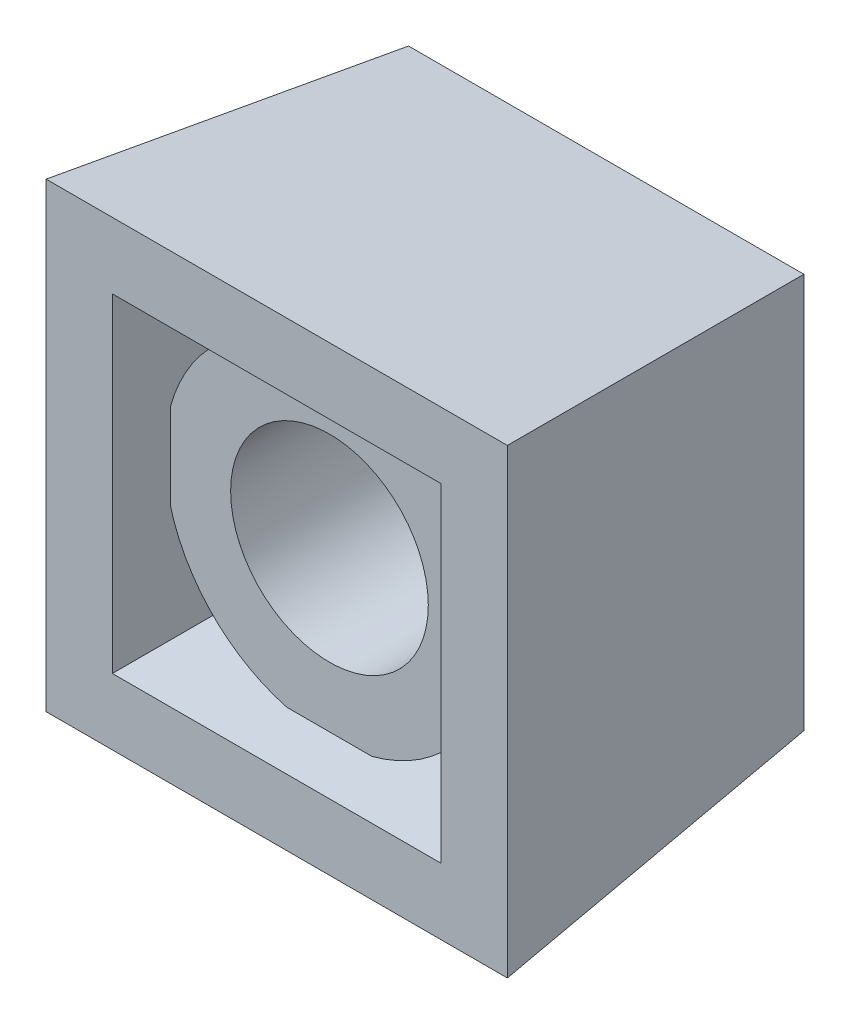
SolidWorks part; units mm, degrees
ref_plane "Plan de face" through (0, 0, 0) normal (0, 0, 1) x (1, 0, 0)
ref_plane "Plan de dessus" through (0, 0, 0) normal (0, 1, 0) x (1, 0, 0)
ref_plane "Plan de droite" through (0, 0, 0) normal (1, 0, 0) x (0, 0, -1)
sketch "Esquisse1" plane through (0, 0, 0) normal (0, 0, 1) x (1, 0, 0)
  line L1 (-3, 3) -> (3, 3)
  line L2 (-3, 3) -> (-3, -3)
  line L3 (-3, -3) -> (3, -3)
  line L4 (3, 3) -> (3, -3)
  line L5 (-3, 3) -> (3, -3) construction
  line L6 (-3, -3) -> (3, 3) construction
  point P0 (0, 0)
  dimension "D1" = 6
ref_plane "Plan1" through (0, 0, 5) normal (0, 0, 1) x (1, 0, 0)
sketch "Esquisse2" plane through (0, 0, 5) normal (0, 0, 1) x (1, 0, 0)
  line L1 (3.5, 3.5) -> (-3.5, 3.5)
  line L2 (3.5, 3.5) -> (3.5, -3.5)
  line L3 (3.5, -3.5) -> (-3.5, -3.5)
  line L4 (-3.5, 3.5) -> (-3.5, -3.5)
  line L5 (3.5, 3.5) -> (-3.5, -3.5) construction
  line L6 (3.5, -3.5) -> (-3.5, 3.5) construction
  point P0 (0, 0)
  dimension "D1" = 7
loft "Lissage1" add profiles "Esquisse2", "Esquisse1"
shell "Coque1" thickness 1
sketch "Esquisse3" plane through (0, 0, 1) normal (0, 0, 1) x (1, 0, 0)
  circle A0 centre (0, 0) radius 1.5
  circle A1 centre (0, 0) radius 2.5
  dimension "D1" = 3
  dimension "D2" = 5
extrude "Boss.-Extru.1" add sketch "Esquisse3" along normal blind 3.2
